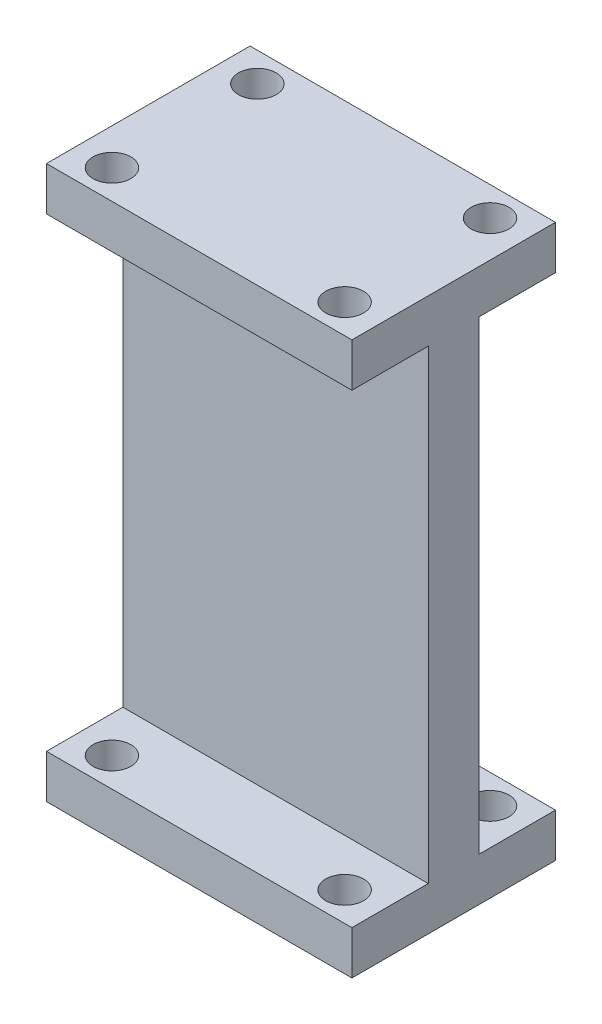
SolidWorks part; units mm, degrees
ref_plane "Front Plane" through (0, 0, 0) normal (0, 0, 1) x (1, 0, 0)
ref_plane "Top Plane" through (0, 0, 0) normal (0, 1, 0) x (1, 0, 0)
ref_plane "Right Plane" through (0, 0, 0) normal (1, 0, 0) x (0, 0, -1)
sketch "Sketch3" plane through (0, 0, 0) normal (0, 1, 0) x (1, 0, 0)
  line L0 (-10.5, 0) -> (10.5, 0) construction
  line L1 (-10.5, 7) -> (10.5, 7)
  line L2 (-10.5, 7) -> (-10.5, -7)
  line L3 (-10.5, -7) -> (10.5, -7)
  line L4 (10.5, 7) -> (10.5, -7)
  line L5 (-10.5, 7) -> (10.5, -7) construction
  line L6 (-10.5, -7) -> (10.5, 7) construction
  circle A0 centre (-8, -5) radius 1.3
  circle A1 centre (8, -5) radius 1.3
  circle A2 centre (8, 5) radius 1.3
  circle A3 centre (-8, 5) radius 1.3
  point P0 (0, 0)
  point P16 (0, 0)
  point P17 (0, 0)
  dimension "D1" = 2.6
  dimension "D2" = 16
  dimension "D3" = 8
  dimension "D4" = 21
  dimension "D5" = 14
  dimension "D6" = 10
extrude "Boss-Extrude1" add sketch "Sketch3" along normal blind 3
sketch "Sketch4" plane through (0, 3, 0) normal (0, 1, 0) x (1, 0, 0)
  line L5 (10.5, -7) -> (10.5, 7) construction
  line L6 (-10.5, 1.75) -> (10.5, 1.75)
  line L7 (-10.5, 1.75) -> (-10.5, -1.75)
  line L8 (-10.5, -1.75) -> (10.5, -1.75)
  line L9 (10.5, 1.75) -> (10.5, -1.75)
  line L10 (-10.5, 1.75) -> (10.5, -1.75) construction
  line L11 (-10.5, -1.75) -> (10.5, 1.75) construction
  point P0 (0, 0)
  point P1 (0, 0)
  dimension "D1" = 3.5
extrude "Boss-Extrude2" add sketch "Sketch4" along normal blind 32
sketch "Sketch5" plane through (0, 35, 0) normal (0, 1, 0) x (1, 0, 0)
  line L1 (-10.5, 7) -> (10.5, 7)
  line L2 (-10.5, 7) -> (-10.5, -7)
  line L3 (-10.5, -7) -> (10.5, -7)
  line L4 (10.5, 7) -> (10.5, -7)
  line L5 (-10.5, 7) -> (10.5, -7) construction
  line L6 (-10.5, -7) -> (10.5, 7) construction
  circle A0 centre (-8, -5) radius 1.3
  circle A1 centre (-8, 5) radius 1.3
  circle A2 centre (8, 5) radius 1.3
  circle A3 centre (8, -5) radius 1.3
  point P0 (0, 0)
extrude "Boss-Extrude3" add sketch "Sketch5" along normal blind 3
